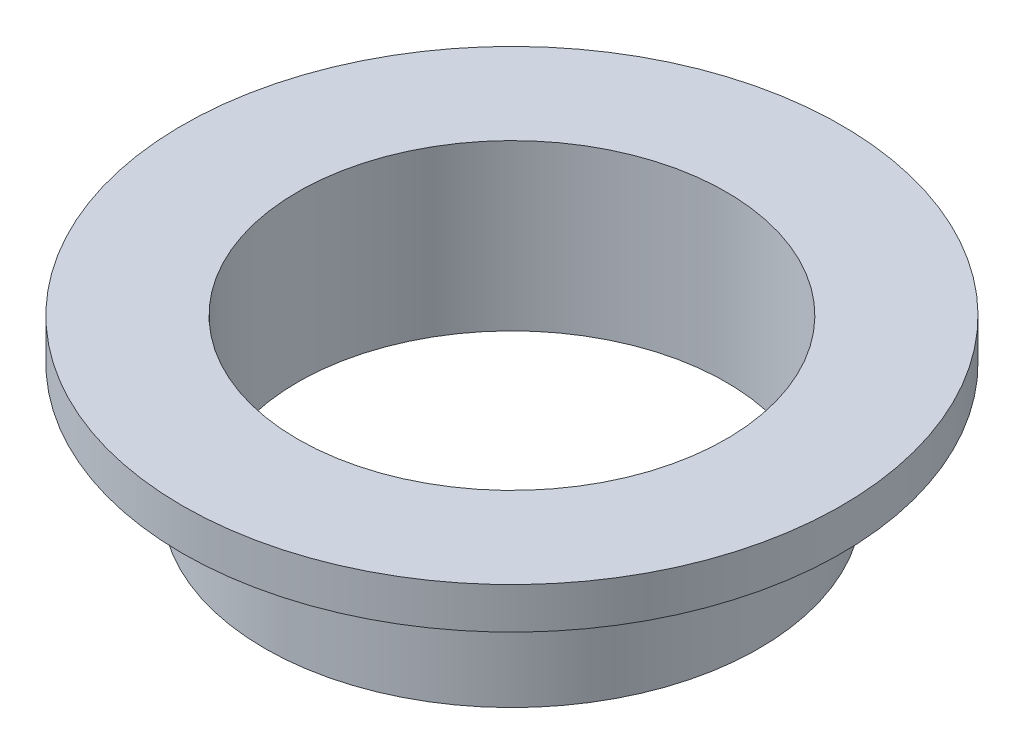
SolidWorks part; units mm, degrees
ref_plane "Front Plane" through (0, 0, 0) normal (0, 0, 1) x (1, 0, 0)
ref_plane "Top Plane" through (0, 0, 0) normal (0, 1, 0) x (1, 0, 0)
ref_plane "Right Plane" through (0, 0, 0) normal (1, 0, 0) x (0, 0, -1)
sketch "Sketch1" plane through (0, 0, 0) normal (0, 1, 0) x (1, 0, 0)
  circle A0 centre (0, 0) radius 2.6
  circle A1 centre (0, 0) radius 3
extrude "Boss-Extrude1" add sketch "Sketch1" along normal blind 1.5
sketch "Sketch2" plane through (0, 1.5, 0) normal (0, 1, 0) x (1, 0, 0)
  circle A0 centre (0, 0) radius 2.6
  circle A1 centre (0, 0) radius 4
extrude "Boss-Extrude2" add sketch "Sketch2" along normal blind 0.5
